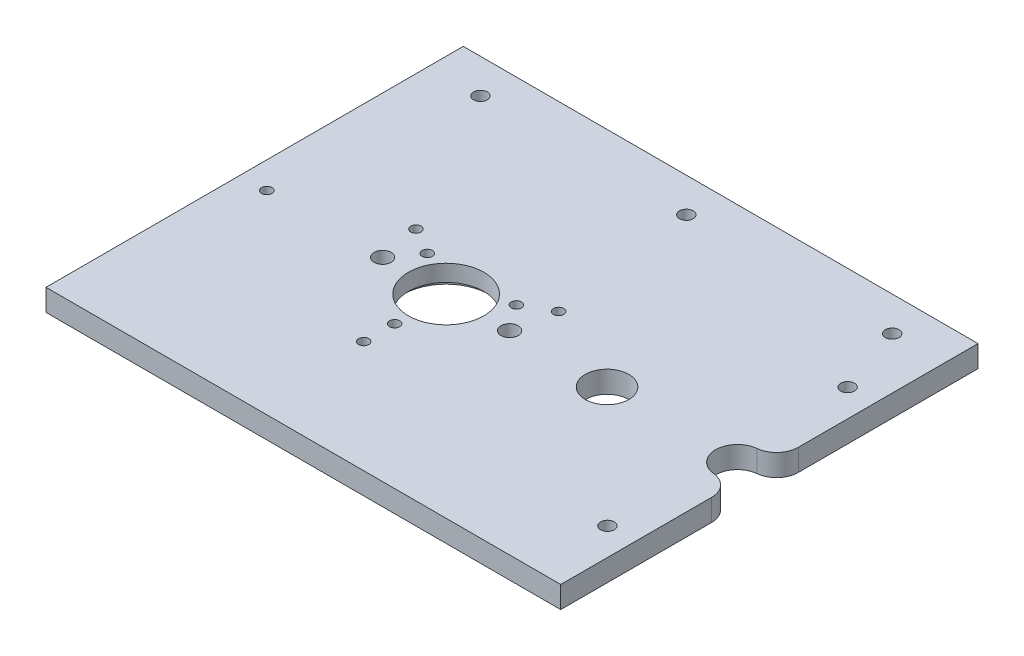
SolidWorks part; units mm, degrees
ref_plane "Alzado" through (0, 0, 0) normal (0, 0, 1) x (1, 0, 0)
ref_plane "Planta" through (0, 0, 0) normal (0, 1, 0) x (1, 0, 0)
ref_plane "Vista lateral" through (0, 0, 0) normal (1, 0, 0) x (0, 0, -1)
sketch "Croquis1" plane through (0, 0, 0) normal (0, 1, 0) x (1, 0, 0)
  line L1 (-75, 50.8) -> (75, 50.8)
  line L2 (-75, 50.8) -> (-75, -50.8)
  line L3 (-75, -50.8) -> (75, -50.8)
  line L4 (75, 50.8) -> (75, -50.8)
  line L5 (-75, 50.8) -> (75, -50.8) construction
  line L6 (-75, -50.8) -> (75, 50.8) construction
  point P0 (0, 0)
  dimension "D1" = 101.6
  dimension "D2" = 150
extrude "Saliente-Extruir1" add sketch "Croquis1" along normal mid plane 6.35
sketch "Croquis2" plane through (0, 3.175, 0) normal (0, 1, 0) x (1, 0, 0)
  line L0 (67, 50.8) -> (67, -50.8) construction
  line L1 (75, 50.8) -> (-75, 50.8) construction
  line L2 (-75, -50.8) -> (75, -50.8) construction
  line L3 (-75, 5.8) -> (75, 5.8) construction
  line L4 (-75, 50.8) -> (-75, -50.8) construction
  line L5 (75, -50.8) -> (75, 50.8) construction
  line L6 (-15, -95.8) -> (-15, 5.8) construction
  line L7 (-75, -50.8) -> (-75, -30.8) construction
  line L8 (-75, -30.8) -> (75, -30.8) construction
  circle A0 centre (67, 40.8) radius 2
  circle A1 centre (67, -29.2) radius 2
  circle A2 centre (-15, 5.8) radius 11
  circle A3 centre (-67.25, 5.8) radius 1.5
  circle A4 centre (31.9, 5.8) radius 6.35
  circle A5 centre (69.9, 5.8) radius 6.35
  circle A6 centre (-15, 5.8) radius 101.6 construction
  dimension "D3" = 4
  dimension "D6" = 22
  dimension "D7" = 3
  dimension "D9" = 12.7
  dimension "D12" = 203.2
  dimension "D2" = 8
  dimension "D4" = 35
  dimension "D5" = 82
  dimension "D8" = 52.25
  dimension "D10" = 46.9
  dimension "D11" = 84.9
  dimension "D13" = 20
  dimension "D14" = 65
  dimension "D15" = 45
extrude "Cortar-Extruir1" cut sketch "Croquis2" against normal through all
fillet "Redondeo1" radius 6.35 2 edges at (75, 0, -9.5832) (75, 0, -2.0168)
sketch "Croquis3" plane through (0, 3.175, 0) normal (0, 1, 0) x (1, 0, 0)
  line L0 (-15, 5.8) -> (-15, -18.2) construction
  circle A0 centre (-15, -9.2) radius 1.5
  circle A1 centre (-15, -18.2) radius 1.5
  circle A2 centre (-15, 5.8) radius 20 construction
  circle A3 centre (-15, -18.2) radius 4 construction
  circle A4 centre (-27.9904, 13.3) radius 1.5
  circle A5 centre (-35.7846, 17.8) radius 1.5
  circle A6 centre (-2.0096, 13.3) radius 1.5
  circle A7 centre (5.7846, 17.8) radius 1.5
  point P19 (-15, 5.8)
  dimension "D1" = 3
  dimension "D2" = 3
  dimension "D5" = 40
  dimension "D6" = 8
  dimension "D3" = 15
  dimension "D4" = 24
  dimension "D7" = 3
extrude "Cortar-Extruir2" cut sketch "Croquis3" against normal through all
sketch "Croquis4" plane through (0, 0, 0) normal (0, 1, 0) x (1, 0, 0)
  circle A0 centre (-15, 5.8) radius 12.5
  dimension "D1" = 25
extrude "Cortar-Extruir3" cut sketch "Croquis4" along normal blind 1.5 from surface at -3.175 starting at face at (5.7846, -3.175, -16.3)
sketch "Croquis7" plane through (0, -3.175, 0) normal (0, -1, 0) x (1, 0, 0)
  line L0 (-15, -5.8) -> (-15, -60.8) construction
  line L1 (75, -50.8) -> (-75, -50.8) construction
  line L2 (-125, -50.8) -> (-125, -70.8) construction
  line L9 (-190, -50.8) -> (160, -50.8) construction
  line L10 (-190, -50.8) -> (-190, -70.8) construction
  line L11 (-190, -70.8) -> (160, -70.8) construction
  line L12 (160, -50.8) -> (160, -70.8) construction
  line L13 (-190, -50.8) -> (160, -70.8) construction
  line L14 (-190, -70.8) -> (160, -50.8) construction
  line L15 (-145, -50.8) -> (-145, -70.8) construction
  line L16 (-100, -50.8) -> (-100, -70.8) construction
  line L17 (-15, -107.4) -> (-193.2942, -107.4) construction
  line L18 (-190, -50.8) -> (-190, -30.8) construction
  line L19 (-190, -30.8) -> (-15, -30.8) construction
  line L20 (-15, -70.8) -> (-15, -90.8) construction
  line L21 (-15, -90.8) -> (-52.7811, -90.8) construction
  line L22 (-52.7811, -90.8) -> (-52.7811, -70.8) construction
  circle A0 centre (-15, -5.8) radius 101.6 construction
  circle A1 centre (-125, -82.5) radius 24.9 construction
  circle A2 centre (-165, -82.5) radius 24.9 construction
  dimension "D4" = 45
  dimension "D1" = 203.2
  dimension "D7" = 49.8
  dimension "D2" = 20
  dimension "D3" = 350
  dimension "D5" = 45
  dimension "D6" = 20
  dimension "D8" = 20
  dimension "D9" = 76.6
  dimension "D10" = 20
sketch "Croquis8" plane through (0, -3.175, 0) normal (0, -1, 0) x (1, 0, 0)
  line L0 (-15, -5.8) -> (-15, 6.7) construction
  line L1 (-15, -5.8) -> (3.5, -5.8) construction
  circle A0 centre (-15, -5.8) radius 12.5 construction
  circle A1 centre (3.5, -5.8) radius 2.5
  circle A2 centre (-33.5, -5.8) radius 2.5
  dimension "D2" = 5
  dimension "D1" = 18.5
extrude "Cortar-Extruir5" cut sketch "Croquis8" against normal through all
chamfer "Chaflán2" distance 2.5 angle 45 2 edges at (-33.5, -3.175, -3.3) (3.5, -3.175, -8.3)
sketch "Croquis9" plane through (0, -3.175, 0) normal (0, -1, 0) x (1, 0, 0)
  line L0 (0, -50.8) -> (-75, -50.8)
  line L1 (75, -50.8) -> (-75, -50.8) construction
  line L2 (-75, -50.8) -> (-75, -70.8)
  line L3 (-75, -70.8) -> (75, -70.8)
  line L4 (75, -70.8) -> (75, -50.8)
  line L5 (75, -50.8) -> (0, -50.8)
  line L6 (-75, -60.8) -> (75, -60.8) construction
  circle A0 centre (0, -60.8) radius 2
  circle A1 centre (-60, -60.8) radius 2
  circle A2 centre (60, -60.8) radius 2
  dimension "D2" = 4
  dimension "D1" = 20
  dimension "D3" = 60
  dimension "D4" = 60
extrude "Saliente-Extruir2" add sketch "Croquis9" against normal up to surface (6.35 mm away) up to face at (3.5, 3.175, -8.3)
